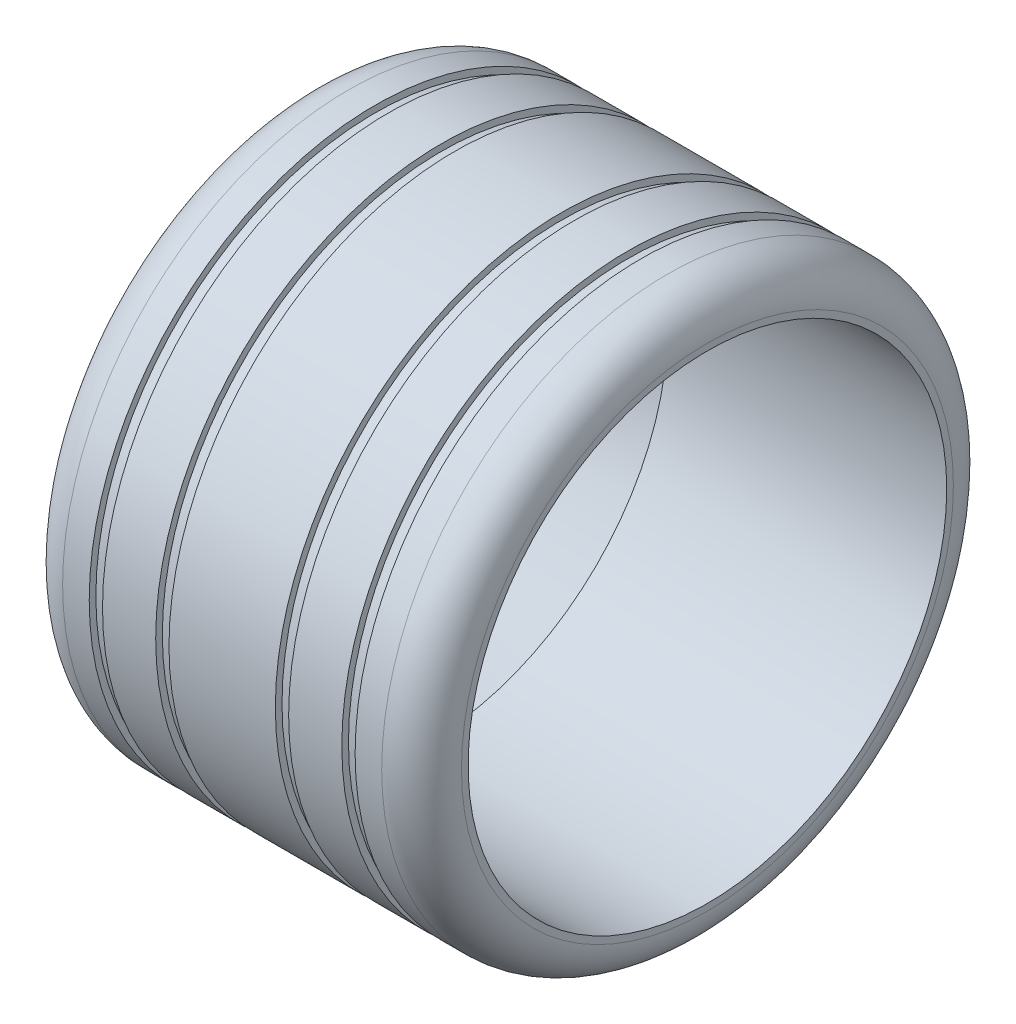
SolidWorks part; units mm, degrees
material "Rubber"
ref_plane "Front Plane" through (0, 0, 0) normal (0, 0, 1) x (1, 0, 0)
ref_plane "Top Plane" through (0, 0, 0) normal (0, 1, 0) x (1, 0, 0)
ref_plane "Right Plane" through (0, 0, 0) normal (1, 0, 0) x (0, 0, -1)
sketch "Sketch1" plane through (0, 0, 0) normal (1, 0, 0) x (0, 0, -1)
  circle A0 centre (0, 0) radius 21.5
  dimension "D1" = 43
extrude "Boss-Extrude1" add sketch "Sketch1" along normal blind 30
sketch "Sketch2" plane through (30, 0, 0) normal (1, 0, 0) x (0, 0, -1)
  circle A0 centre (0, 0) radius 18
  dimension "D1" = 36
extrude "Cut-Extrude1" cut sketch "Sketch2" against normal blind 25
sketch "Sketch4" plane through (0, 0, 0) normal (-1, 0, 0) x (0, 0, 1)
  circle A0 centre (0, 0) radius 10.5
  dimension "D1" = 21
extrude "Cut-Extrude2" cut sketch "Sketch4" against normal through all
fillet "Fillet1" radius 3 2 edges at (0, 0, -21.5) (30, 0, -21.5)
sketch "Sketch5" plane through (0, 0, 0) normal (0, 0, 1) x (1, 0, 0)
  line L0 (27, 21.5) -> (3, 21.5) construction
  line L1 (5, 21.5) -> (6, 21.5)
  line L2 (5, 21.5) -> (5, 21)
  line L3 (5, 21) -> (6, 21)
  line L4 (6, 21.5) -> (6, 21)
  line L5 (15, 21.5) -> (15, -21.5) construction
  line L6 (3, -21.5) -> (27, -21.5) construction
  line L7 (0, 0) -> (30, 0) construction
  line L8 (30, -18.5) -> (30, 18.5) construction
  line L9 (24, 21.5) -> (24, 21)
  line L10 (25, 21) -> (24, 21)
  line L11 (25, 21.5) -> (25, 21)
  line L12 (25, 21.5) -> (24, 21.5)
  line L13 (10, 21.5) -> (10, 21)
  line L14 (10, 21) -> (11, 21)
  line L15 (10, 21.5) -> (11, 21.5)
  line L16 (11, 21.5) -> (11, 21)
  line L17 (19, 21.5) -> (19, 21)
  line L18 (20, 21.5) -> (19, 21.5)
  line L19 (20, 21) -> (19, 21)
  line L20 (20, 21.5) -> (20, 21)
  dimension "D1" = 1
  dimension "D2" = 0.5
  dimension "D3" = 10
  dimension "D5" = 5
  dimension "D4" = 2
revolve "Cut-Revolve1" cut sketch "Sketch5" angle 360 about L7
chamfer "Chamfer1" distance 4 angle 20 1 edges at (5, 0, -18)
